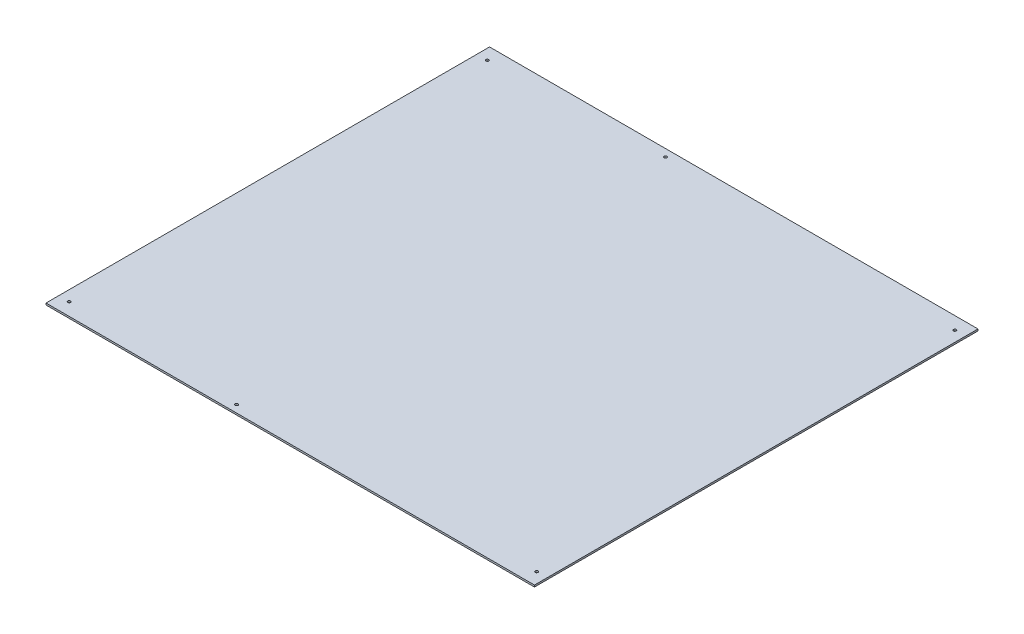
SolidWorks part; units mm, degrees
ref_plane "Alzado" through (0, 0, 0) normal (0, 0, 1) x (1, 0, 0)
ref_plane "Planta" through (0, 0, 0) normal (0, 1, 0) x (1, 0, 0)
ref_plane "Vista lateral" through (0, 0, 0) normal (1, 0, 0) x (0, 0, -1)
sketch "Croquis1" plane through (0, 0, 0) normal (0, 1, 0) x (1, 0, 0)
  line L1 (0, 0) -> (550.5, 0)
  line L2 (0, 0) -> (0, 500)
  line L3 (0, 500) -> (550.5, 500)
  line L4 (550.5, 0) -> (550.5, 500)
  dimension "D1" = 500
  dimension "D2" = 550.5
extrude "Saliente-Extruir1" add sketch "Croquis1" along normal blind 2
sketch "Croquis2" plane through (0, 2, 0) normal (0, 1, 0) x (1, 0, 0)
  line L0 (550.5, 500) -> (0, 500) construction
  line L1 (0, 500) -> (0, 0) construction
  line L2 (275.25, 500) -> (275.25, 0) construction
  line L3 (0, 0) -> (550.5, 0) construction
  line L4 (0, 250) -> (550.5, 250) construction
  line L5 (550.5, 0) -> (550.5, 500) construction
  circle A0 centre (12.5, 485) radius 1.55
  circle A1 centre (538, 485) radius 1.55
  circle A2 centre (538, 15) radius 1.55
  circle A3 centre (12.5, 15) radius 1.55
  dimension "D1" = 3.1
  dimension "D2" = 15
  dimension "D3" = 12.5
extrude "Cortar-Extruir1" cut sketch "Croquis2" against normal up to surface (2 mm away) up to face at (275.25, 0, -250)
sketch "Croquis3" plane through (0, 2, 0) normal (0, 1, 0) x (1, 0, 0)
  line L0 (549.75, 499.25) -> (0.75, 499.25)
  line L1 (0.75, 499.25) -> (0.75, 0.75)
  line L2 (0.75, 0.75) -> (549.75, 0.75)
  line L3 (549.75, 0.75) -> (549.75, 499.25)
  line L4 (0, 500) -> (0, 0)
  line L5 (0, 0) -> (550.5, 0)
  line L6 (550.5, 0) -> (550.5, 500)
  line L7 (550.5, 500) -> (0, 500)
  line L8 (0, 500) -> (0, 0)
  line L9 (0, 0) -> (550.5, 0)
  line L10 (550.5, 0) -> (550.5, 500)
  line L11 (550.5, 500) -> (0, 500)
  dimension "D1" = 0
  dimension "D2" = 0.75
extrude "Cortar-Extruir2" cut sketch "Croquis3" against normal up to surface (2 mm away) up to face at (12.5, 0, -16.55)
sketch "Croquis4" plane through (0, 2, 0) normal (0, 1, 0) x (1, 0, 0)
  line L0 (0.75, 0.75) -> (549.75, 0.75) construction
  line L1 (549.75, 499.25) -> (0.75, 499.25) construction
  line L2 (0.75, 499.25) -> (0.75, 0.75) construction
  circle A0 centre (206.75, 491) radius 1.6
  circle A1 centre (206.75, 9) radius 1.6
  dimension "D1" = 3.2
  dimension "D2" = 3.2
  dimension "D3" = 8.25
  dimension "D4" = 8.25
  dimension "D5" = 206
  dimension "D6" = 206
extrude "Cortar-Extruir3" cut sketch "Croquis4" against normal up to surface (2 mm away) up to face at (12.5, 0, -486.55)
